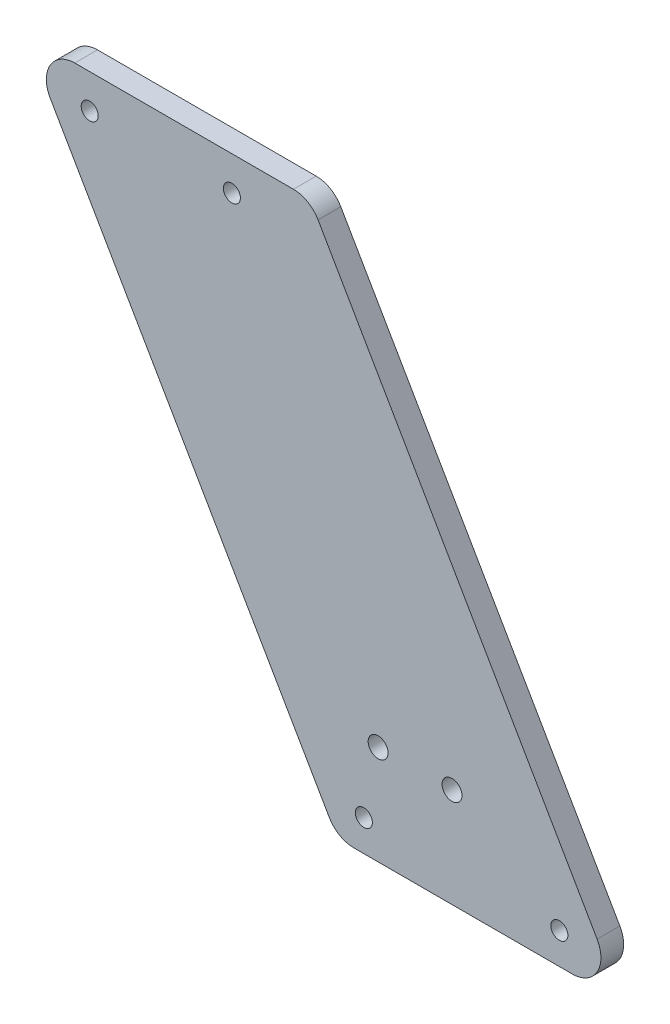
SolidWorks part; units mm, degrees
material "Pin"
ref_plane "Plan de face" through (0, 0, 0) normal (0, 0, 1) x (1, 0, 0)
ref_plane "Plan de dessus" through (0, 0, 0) normal (0, 1, 0) x (1, 0, 0)
ref_plane "Plan de droite" through (0, 0, 0) normal (1, 0, 0) x (0, 0, -1)
sketch "Esquisse1" plane through (0, 0, 0) normal (0, 0, 1) x (1, 0, 0)
  line L8 (-38.453, 0) -> (38.453, 0)
  line L13 (-47.1132, -15) -> (51.0363, -185)
  line L14 (47.1132, -5) -> (145.2628, -175)
  line L15 (59.6966, -190) -> (136.6025, -190)
  arc A11 (38.453, 0) -> (47.1132, -5) centre (38.453, -10) cw
  arc A12 (-47.1132, -15) -> (-38.453, 0) centre (-38.453, -10) cw
  arc A13 (51.0363, -185) -> (59.6966, -190) centre (59.6966, -180) ccw
  arc A14 (145.2628, -175) -> (136.6025, -190) centre (136.6025, -180) cw
  point P6 (0, 0)
  point P9 (44.2265, 0)
  point P12 (-55.7735, 0)
  dimension "D1" = 190
  dimension "D5" = 10
  dimension "D3" = 60
  dimension "D4" = 10
  dimension "D2" = 100
extrude "Boss.-Extru.1" add sketch "Esquisse1" along normal blind 8
extrude "Enlèv. mat.-Extru.1" cut sketch "Esquisse2" against normal through all
sketch "Esquisse2" plane through (81.2326, -630, 8) normal (0, 0, 1) x (1, 0, 0)
  line L1 (-128.3459, 625) -> (-93.8111, 607.6308) construction
  line L3 (-114.4279, 618) -> (-18.0105, 451) construction
  line L4 (-42.0939, 611.8123) -> (50.7511, 451) construction
  circle A0 centre (-114.4279, 618) radius 3
  circle A1 centre (-64.4279, 618) radius 3
  arc A4 (-8.5, 477.9325) -> (-17.5, 477.9325) centre (-13, 477.9325) ccw construction
  arc A5 (17.5, 477.9325) -> (8.5, 477.9325) centre (13, 477.9325) ccw construction
  circle A6 centre (-13, 474.9325) radius 3.5
  circle A7 centre (13, 474.9325) radius 3.5
  circle A9 centre (-18.0105, 451) radius 3
  circle A10 centre (50.7511, 451) radius 3
  point P30 (0, 0)
